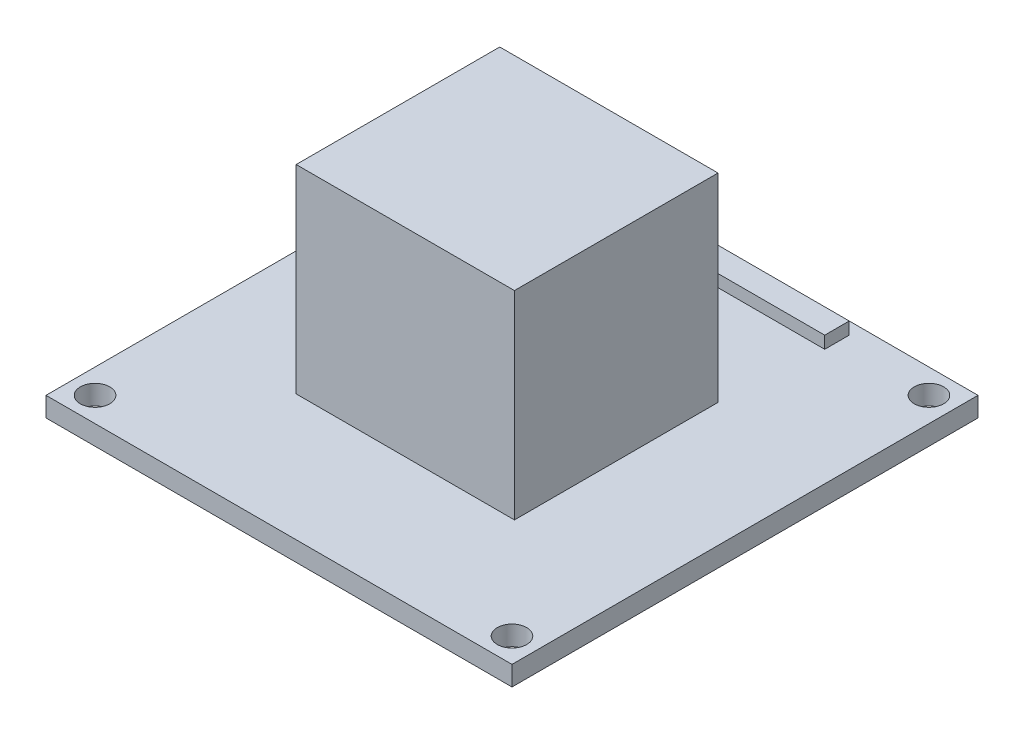
SolidWorks part; units mm, degrees
ref_plane "Front Plane" through (0, 0, 0) normal (0, 0, 1) x (1, 0, 0)
ref_plane "Top Plane" through (0, 0, 0) normal (0, 1, 0) x (1, 0, 0)
ref_plane "Right Plane" through (0, 0, 0) normal (1, 0, 0) x (0, 0, -1)
sketch "Sketch2" plane through (0, 0, 0) normal (0, 1, 0) x (1, 0, 0)
  line L0 (-17, 17) -> (17, 17) construction
  line L1 (-19, 19) -> (19, 19)
  line L2 (-19, 19) -> (-19, -19)
  line L3 (-19, -19) -> (19, -19)
  line L4 (19, 19) -> (19, -19)
  line L5 (0, -19) -> (0, 19) construction
  line L6 (-19, 0) -> (19, 0) construction
  line L7 (-17, 17) -> (-17, -17) construction
  circle A0 centre (-17, 17) radius 1.2
  circle A1 centre (17, 17) radius 1.2
  circle A2 centre (17, -17) radius 1.2
  circle A3 centre (-17, -17) radius 1.2
  point P4 (-16.5821, 16.7144)
  point P5 (0, 17)
  point P7 (-17, 0)
  point P108 (0, 0)
  dimension "D2" = 2.4
  dimension "D3" = 2
  dimension "D1" = 38
  dimension "D5" = 90
  dimension "D6" = 34
  dimension "D7" = 34
  dimension "D4" = 2
extrude "Boss-Extrude1" add sketch "Sketch2" along normal blind 1.6
sketch "Sketch3" plane through (0, 1.6, 0) normal (0, 1, 0) x (1, 0, 0)
  line L0 (-19, -19) -> (19, -19) construction
  line L1 (-8.9, 7.9) -> (8.9, 7.9)
  line L2 (-8.9, 7.9) -> (-8.9, -8.7)
  line L3 (-8.9, -8.7) -> (8.9, -8.7)
  line L4 (8.9, 7.9) -> (8.9, -8.7)
  line L5 (0, -8.7) -> (0, 7.9) construction
  line L6 (-8.9, -0.4) -> (8.9, -0.4) construction
  point P124 (0, -0.4)
  dimension "D1" = 17.8
  dimension "D2" = 16.6
  dimension "D3" = 10.3
extrude "Boss-Extrude2" add sketch "Sketch3" along normal blind 16.2
sketch "Sketch4" plane through (0, 1.6, 0) normal (0, 1, 0) x (1, 0, 0)
  line L0 (19, 19) -> (-19, 19) construction
  line L1 (-9.5, 18) -> (9.5, 18)
  line L2 (-9.5, 18) -> (-9.5, 16)
  line L3 (-9.5, 16) -> (9.5, 16)
  line L4 (9.5, 18) -> (9.5, 16)
  line L5 (0, 16) -> (0, 18) construction
  line L6 (-9.5, 17) -> (9.5, 17) construction
  point P160 (0, 17)
  dimension "D1" = 19
  dimension "D2" = 2
  dimension "D3" = 1
  dimension "D4" = 17
extrude "Boss-Extrude3" add sketch "Sketch4" along normal blind 1
